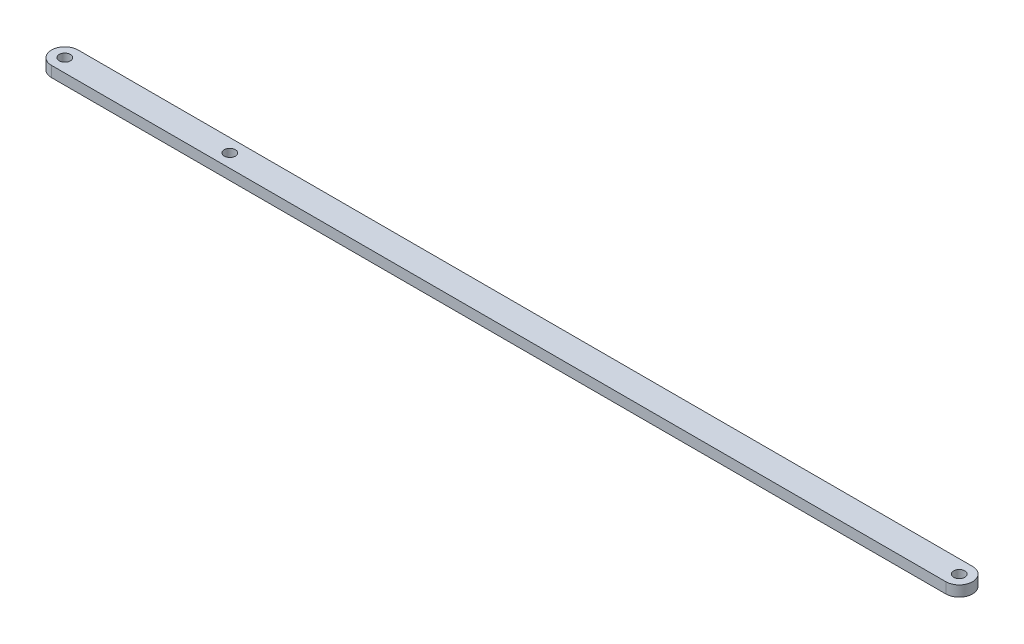
SolidWorks part; units mm, degrees
ref_plane "Front Plane" through (0, 0, 0) normal (0, 0, 1) x (1, 0, 0)
ref_plane "Top Plane" through (0, 0, 0) normal (0, 1, 0) x (1, 0, 0)
ref_plane "Right Plane" through (0, 0, 0) normal (1, 0, 0) x (0, 0, -1)
sketch "Sketch1" plane through (0, 0, 0) normal (0, 1, 0) x (1, 0, 0)
  line L0 (0, 0) -> (168, 0) construction
  line L1 (0, 2.5) -> (168, 2.5)
  line L2 (0, -2.5) -> (168, -2.5)
  arc A0 (0, 2.5) -> (0, -2.5) centre (0, 0) ccw
  arc A1 (168, -2.5) -> (168, 2.5) centre (168, 0) ccw
  circle A2 centre (0, 0) radius 1.05
  circle A3 centre (168, 0) radius 1.05
  circle A4 centre (31, 0) radius 1.05
  point P3 (84, 0)
  dimension "D1" = 2.5
  dimension "D3" = 2.1
  dimension "D4" = 2.1
  dimension "D5" = 31
  dimension "D2" = 168
extrude "Boss-Extrude1" add sketch "Sketch1" along normal blind 2
